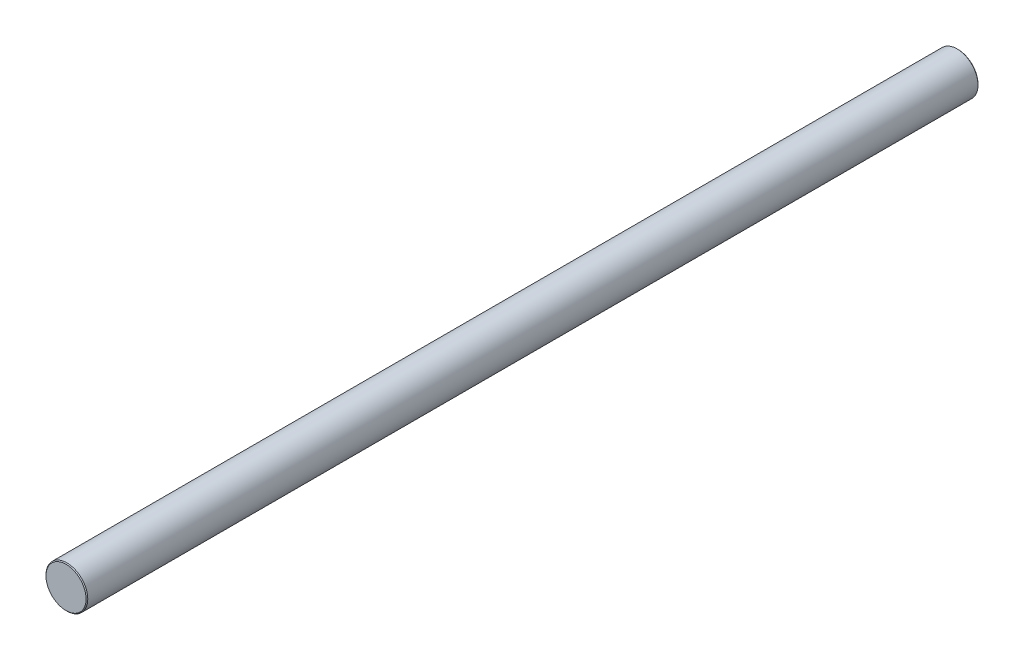
SolidWorks part; units mm, degrees
ref_plane "Front Plane" through (0, 0, 0) normal (0, 0, 1) x (1, 0, 0)
ref_plane "Top Plane" through (0, 0, 0) normal (0, 1, 0) x (1, 0, 0)
ref_plane "Right Plane" through (0, 0, 0) normal (1, 0, 0) x (0, 0, -1)
sketch "Sketch1" plane through (0, 0, 0) normal (0, 1, 0) x (0, 0, -1)
  line L0 (0, 0) -> (0, 4.7625) construction
  line L1 (-101.6, 4.7625) -> (101.6, 4.7625)
  line L2 (-101.6, 4.7625) -> (-101.6, -4.7625)
  line L3 (-101.6, -4.7625) -> (101.6, -4.7625)
  line L4 (101.6, 4.7625) -> (101.6, -4.7625)
  line L5 (-101.6, 4.7625) -> (101.6, -4.7625) construction
  line L6 (-101.6, -4.7625) -> (101.6, 4.7625) construction
  line L7 (0, 0) -> (0, -4.7625) construction
  point P0 (0, 0)
  point P8 (-90.6462, 4.7625)
  point P10 (90.6463, 4.7625)
  point P11 (-86.995, 0)
  point P12 (88.9517, 0)
  dimension "Diameter" = 9.525
  dimension "Length" = 203.2
  dimension "D1" = 10.9537
  dimension "D2" = 10.9537
  dimension "D3" = 12.6483
  dimension "D4" = 14.605
sketch "Sketch3" plane through (0, 0, 0) normal (0, 0, 1) x (1, 0, 0)
  line L0 (-4.7625, 0) -> (4.7625, 0) construction
  circle A2 centre (0, 0) radius 4.7625
extrude "Boss-Extrude1" add sketch "Sketch3" along normal up to vertex (101.6 mm away) and the other way up to vertex (101.6 mm away) up to point (-4.7625, 0, 101.6) other way up to point (-4.7625, 0, -101.6)
chamfer "Chamfer1" distance 0.1905 angle 45 2 edges at (4.7625, 0, -101.6) (4.7625, 0, 101.6)
equation "\"D2@Sketch1\"=1.15*\"Diameter@Sketch1\""
equation "\"D1@Sketch1\"=\"D2@Sketch1\""
equation "\"D1@Chamfer1\"=\"Diameter@Sketch1\"*.02"
equation "\"D3@Sketch1\"=\"D2@Sketch1\"/(2*tan(.5236*180/pi))*4/3"
equation "\"D4@Sketch1\"=4/3*\"D2@Sketch1\""
